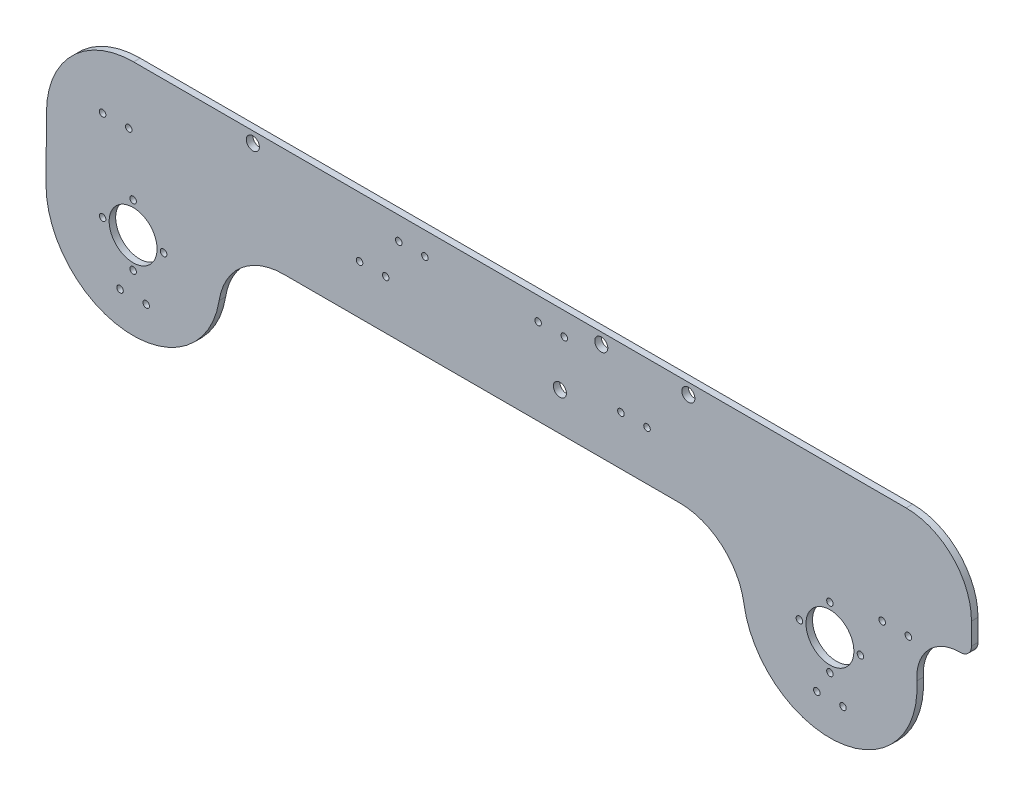
SolidWorks part; units mm, degrees
ref_plane "前视基准面" through (0, 0, 0) normal (0, 0, 1) x (1, 0, 0)
ref_plane "上视基准面" through (0, 0, 0) normal (0, 1, 0) x (1, 0, 0)
ref_plane "右视基准面" through (0, 0, 0) normal (1, 0, 0) x (0, 0, -1)
sketch "Model" plane through (0, 0, 0) normal (0, 0, 1) x (1, 0, 0)
  line L3 (69.1303, 19) -> (250.8697, 19)
  line L4 (0.222, 68.9969) -> (355, 68.9969)
  line L5 (-39.778, 28.9969) -> (-40, 0)
  line L6 (385, 38.9969) -> (385, 29)
  line L7 (380, 24) -> (379.8665, 24)
  arc A15 (0.222, 68.9969) -> (-39.778, 28.9969) centre (0.222, 28.9969) ccw
  circle A16 centre (344, 18.5) radius 1.5
  circle A17 centre (356, 18.5) radius 1.5
  circle A18 centre (326, -24.5) radius 1.5
  circle A19 centre (314, -24.5) radius 1.5
  arc A20 (385, 38.9969) -> (355, 68.9969) centre (355, 38.9969) ccw
  arc A21 (379.8665, 24) -> (359.911, 2.6667) centre (379.8665, 4) ccw
  arc A22 (380, 24) -> (385, 29) centre (380, 29) ccw
  circle A23 centre (198, 58.4969) radius 1.5
  circle A24 centre (186, 58.4969) radius 1.5
  circle A25 centre (122, 58.4969) radius 1.5
  circle A26 centre (134, 58.4969) radius 1.5
  circle A27 centre (215, 63.9969) radius 3
  circle A28 centre (54.9832, 63.9969) radius 3
  circle A29 centre (0, 0) radius 11
  circle A30 centre (0, 14) radius 1.5
  circle A31 centre (14, 0) radius 1.5
  circle A32 centre (0, -14) radius 1.5
  circle A33 centre (-14, 0) radius 1.5
  circle A34 centre (320, 0) radius 11
  circle A35 centre (320, 14) radius 1.5
  circle A36 centre (334, 0) radius 1.5
  circle A37 centre (320, -14) radius 1.5
  circle A38 centre (306, 0) radius 1.5
  arc A39 (-39.9953, 0.6124) -> (39.503, -6.2857) centre (0, 0) ccw
  arc A40 (280.497, -6.2857) -> (359.911, 2.6667) centre (320, 0) ccw
  arc A41 (69.1303, 19) -> (39.503, -6.2857) centre (69.1303, -11) ccw
  arc A42 (280.497, -6.2857) -> (250.8697, 19) centre (250.8697, -11) ccw
  circle A43 centre (196, 36.5) radius 3
  circle A44 centre (116, 41.5) radius 1.5
  circle A45 centre (104, 41.5) radius 1.5
  circle A46 centre (255, 63.9969) radius 3
  circle A47 centre (-2, 41.5) radius 1.5
  circle A48 centre (-14, 41.5) radius 1.5
  circle A49 centre (6, -24.5) radius 1.5
  circle A50 centre (-6, -24.5) radius 1.5
  circle A51 centre (236, 41.5) radius 1.5
  circle A52 centre (224, 41.5) radius 1.5
  dimension "D1" = 22
extrude "凸台-拉伸1" add sketch "Model" along normal blind 3 contours A42 A40 A21 L7 A22 L6 A20 L4 A15 L5 A39 A41 L3 A52 A51 A50 A49 A48 A47 A46 A45 A44 A43 A38 A37 A36 A35 A34 A33 A32 A31
